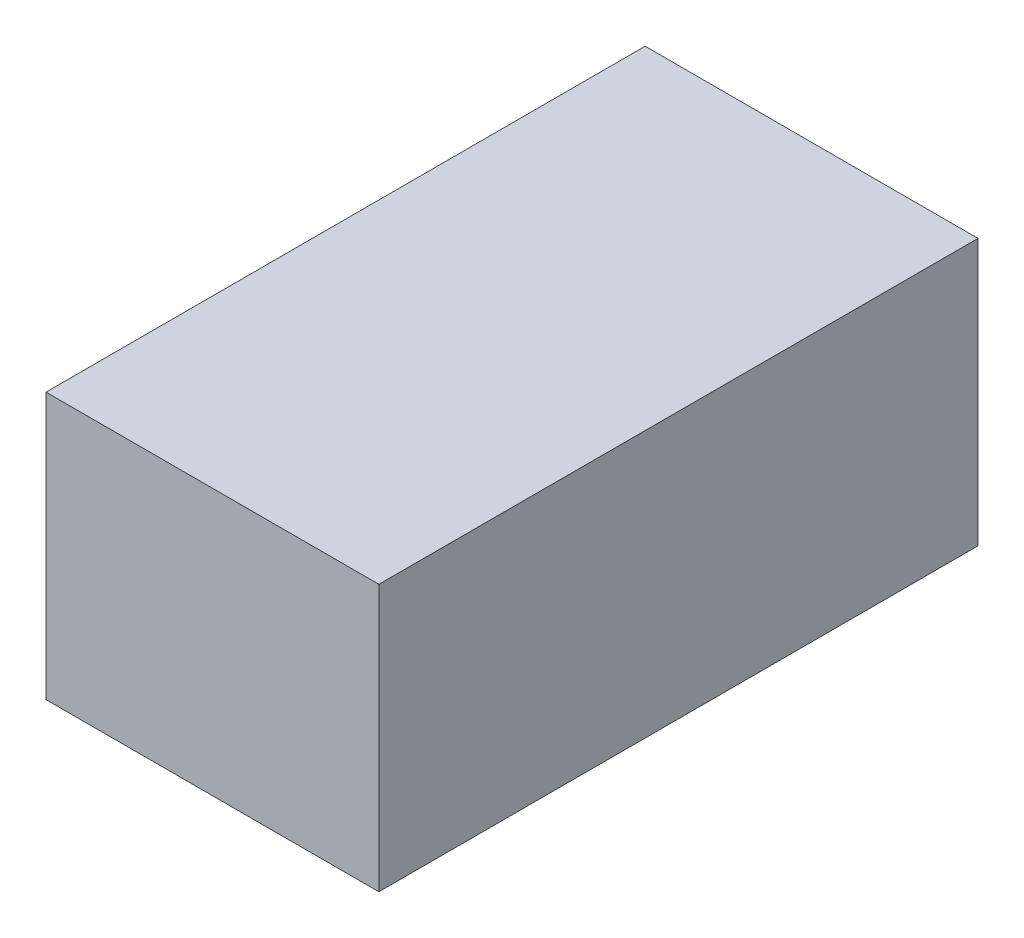
SolidWorks part; units mm, degrees
ref_plane "Front Plane" through (0, 0, 0) normal (0, 0, 1) x (1, 0, 0)
ref_plane "Top Plane" through (0, 0, 0) normal (0, 1, 0) x (1, 0, 0)
ref_plane "Right Plane" through (0, 0, 0) normal (1, 0, 0) x (0, 0, -1)
sketch "Sketch1" plane through (0, 0, 0) normal (0, 0, 1) x (1, 0, 0)
  line L1 (0, 0) -> (30, 0)
  line L2 (0, 0) -> (0, 24)
  line L3 (0, 24) -> (30, 24)
  line L4 (30, 0) -> (30, 24)
  dimension "D1" = 24
  dimension "D2" = 30
extrude "Boss-Extrude1" add sketch "Sketch1" along normal blind 54
sketch "Sketch3" plane through (0, 0, 0) normal (0, 0, -1) x (-1, 0, 0)
  line L0 (-15, 24) -> (-15, 0) construction
  line L1 (-30, 24) -> (0, 24) construction
  line L2 (0, 0) -> (-30, 0) construction
  line L4 (-30, 0) -> (-30, 24) construction
  line L5 (-30, 12) -> (0, 12) construction
  line L6 (0, 24) -> (0, 0) construction
  point P6 (-15, 12)
